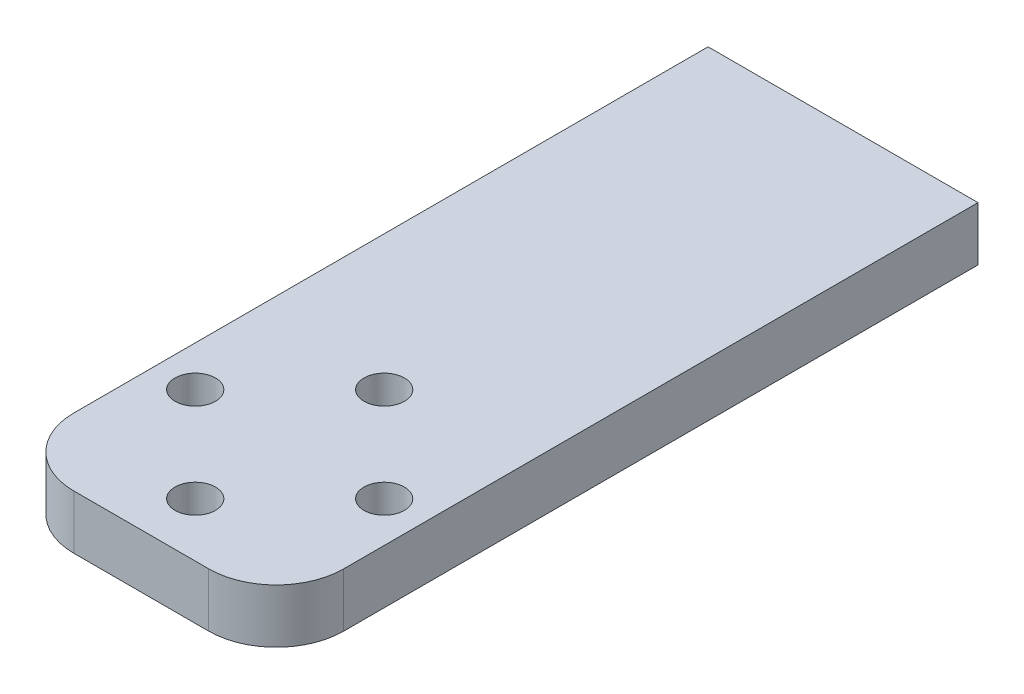
SolidWorks part; units mm, degrees
ref_plane "Front Plane" through (0, 0, 0) normal (0, 0, 1) x (1, 0, 0)
ref_plane "Top Plane" through (0, 0, 0) normal (0, 1, 0) x (1, 0, 0)
ref_plane "Right Plane" through (0, 0, 0) normal (1, 0, 0) x (0, 0, -1)
sketch "Sketch1" plane through (0, 0, 0) normal (0, 1, 0) x (1, 0, 0)
  line L1 (-10, 26) -> (10, 26)
  line L2 (-10, 26) -> (-10, -26)
  line L3 (-10, -26) -> (10, -26)
  line L4 (10, 26) -> (10, -26)
  line L5 (-10, 26) -> (10, -26) construction
  line L6 (-10, -26) -> (10, 26) construction
  circle A0 centre (0, -22) radius 1.5
  circle A1 centre (0, -8) radius 1.5
  circle A2 centre (7, -15) radius 1.5
  circle A3 centre (-7, -15) radius 1.5
  point P0 (0, 0)
  point P14 (0, 0)
  point P15 (0, 0)
  point P16 (0, 0)
  point P17 (0, 0)
  point P18 (0, -5.8741)
  dimension "D2" = 3
  dimension "D3" = 3
  dimension "D4" = 3
  dimension "D5" = 3
  dimension "D1" = 20
  dimension "D6" = 14
  dimension "D7" = 14
  dimension "D8" = 7
  dimension "D9" = 7
  dimension "D10" = 4
  dimension "D11" = 52
extrude "Boss-Extrude1" add sketch "Sketch1" along normal blind 4
fillet "Fillet1" radius 5 2 edges at (-10, 2, 26) (10, 2, 26)
